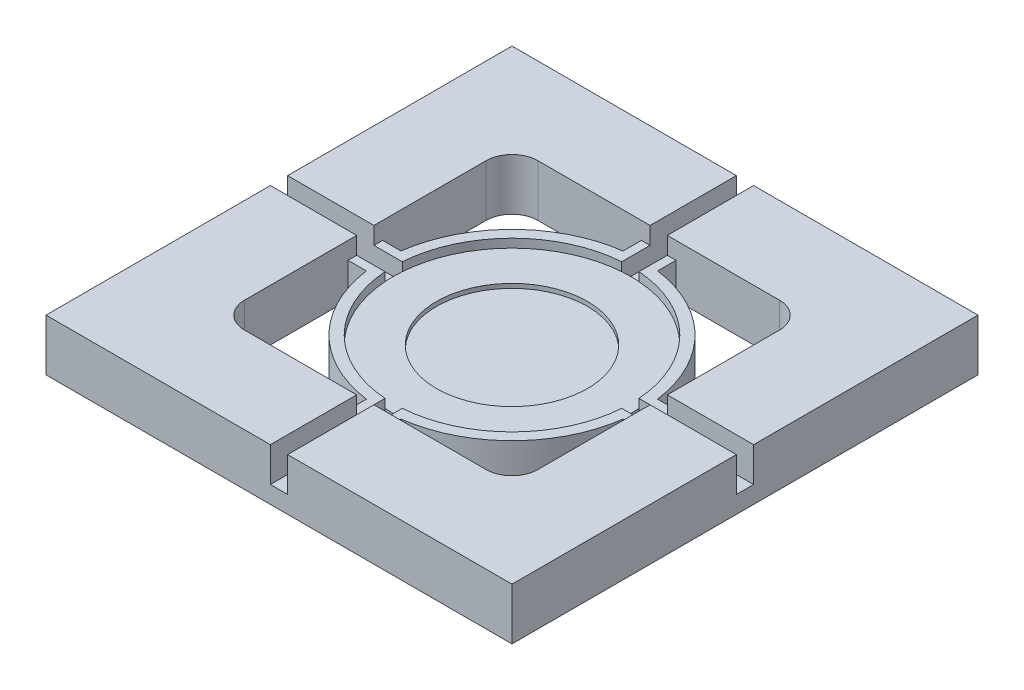
SolidWorks part; units mm, degrees
ref_plane "Front Plane" through (0, 0, 0) normal (0, 0, 1) x (1, 0, 0)
ref_plane "Top Plane" through (0, 0, 0) normal (0, 1, 0) x (1, 0, 0)
ref_plane "Right Plane" through (0, 0, 0) normal (1, 0, 0) x (0, 0, -1)
sketch "Sketch1" plane through (0, 0, 0) normal (0, 1, 0) x (1, 0, 0)
  line L6 (-27, -27) -> (27, -27)
  line L11 (-27, -27) -> (-27, 27)
  line L12 (-27, 27) -> (27, 27)
  line L76 (27, -27) -> (27, 27)
  line L77 (-27, -27) -> (27, 27) construction
  line L78 (-27, 27) -> (27, -27) construction
  point P0 (0, 0)
  dimension "D1" = 54
extrude "Boss-Extrude1" add sketch "Sketch1" along normal blind 10
sketch "Sketch2" plane through (0, 10, 0) normal (0, 1, 0) x (1, 0, 0)
  line L0 (27, 27) -> (-27, 27) construction
  line L1 (-27, 27) -> (-27, -27) construction
  line L2 (-14, -17) -> (14, -17)
  line L3 (-17, -14) -> (-17, 14)
  line L4 (-14, 17) -> (14, 17)
  line L5 (17, -14) -> (17, 14)
  line L6 (-17, -17) -> (17, 17) construction
  line L7 (-17, 17) -> (17, -17) construction
  line L8 (15, 0) -> (17, 0) construction
  line L9 (14.8661, -2) -> (17, -2)
  line L10 (14.8661, 2) -> (17, 2)
  line L11 (15, 2) -> (17, 2) construction
  line L12 (15, -2) -> (17, -2) construction
  line L13 (2, -14.8661) -> (2, -17)
  line L14 (-2, -14.8661) -> (-2, -17)
  line L15 (-14.8661, -2) -> (-17, -2)
  line L16 (-14.8661, 2) -> (-17, 2)
  line L17 (-2, 14.8661) -> (-2, 17)
  line L18 (2, 14.8661) -> (2, 17)
  arc A0 (-2, 14.8661) -> (-14.8661, 2) centre (0, 0) ccw
  arc A1 (-14.8661, -2) -> (-2, -14.8661) centre (0, 0) ccw
  arc A2 (2, -14.8661) -> (14.8661, -2) centre (0, 0) ccw
  arc A3 (14.8661, 2) -> (2, 14.8661) centre (0, 0) ccw
  arc A4 (-14, -17) -> (-17, -14) centre (-14, -14) cw
  arc A5 (14, -17) -> (17, -14) centre (14, -14) ccw
  arc A6 (14, 17) -> (17, 14) centre (14, 14) cw
  arc A7 (-17, 14) -> (-14, 17) centre (-14, 14) cw
  point P4 (0, 0)
  dimension "D3" = 30
  dimension "D8" = 3
  dimension "D1" = 34
  dimension "D2" = 10
  dimension "D7" = 10
  dimension "D4" = 2
  dimension "D5" = 2
  dimension "D6" = 4
extrude "Cut-Extrude2" cut sketch "Sketch2" against normal through all contours A3 L10 L5 L4 L18 | A2 L13 L2 L5 L9 | A1 L15 L3 L2 L14 | A0 L17 L4 L3 L16
sketch "Sketch3" plane through (0, 10, 0) normal (0, 1, 0) x (1, 0, 0)
  line L5 (-14, -17) -> (14, -17)
  line L6 (-17, -14) -> (-17, 14)
  line L7 (-14, 17) -> (14, 17)
  line L8 (17, -14) -> (17, 14)
  line L9 (-17, -17) -> (17, 17) construction
  line L10 (-17, 17) -> (17, -17) construction
  arc A0 (-17, 14) -> (-14, 17) centre (-14, 14) cw
  arc A1 (-14, -17) -> (-17, -14) centre (-14, -14) cw
  arc A2 (14, -17) -> (17, -14) centre (14, -14) ccw
  arc A3 (14, 17) -> (17, 14) centre (14, 14) cw
  point P0 (0, 0)
  dimension "D1" = 3
  dimension "D2" = 28
extrude "Cut-Extrude3" cut sketch "Sketch3" against normal blind 2
sketch "Sketch4" plane through (0, 8, 0) normal (0, 1, 0) x (1, 0, 0)
  circle A0 centre (0, 0) radius 13.75
  dimension "D1" = 27.5
extrude "Cut-Extrude4" cut sketch "Sketch4" against normal blind 1
sketch "Sketch5" plane through (0, 10, 0) normal (0, 1, 0) x (1, 0, 0)
  line L0 (-13.75, 0) -> (-27, 0) construction
  line L1 (-27, 27) -> (-27, -27) construction
  line L2 (0, 27) -> (0, 13.75) construction
  line L3 (27, 27) -> (-27, 27) construction
  line L4 (27, -27) -> (27, 27) construction
  line L5 (-14, 17) -> (14, 17) construction
  line L8 (-1, 27) -> (-1, 13.7136)
  line L9 (-27, -1) -> (-13.7136, -1)
  line L10 (1, 27) -> (1, 13.7136)
  line L11 (-27, 1) -> (-13.7136, 1)
  line L12 (-1, 27) -> (1, 27)
  line L14 (-27, -1) -> (-27, 1)
  line L16 (13.7136, 1) -> (27, 1)
  line L18 (13.75, 0) -> (27, 0) construction
  line L20 (13.7136, -1) -> (27, -1)
  line L22 (1, -13.7136) -> (1, -27)
  line L23 (1, 27) -> (1, -100) construction
  line L24 (0, -13.75) -> (0, -27) construction
  line L25 (0, 27) -> (0, -100) construction
  line L26 (-1, -13.7136) -> (-1, -27)
  line L27 (-1, 27) -> (-1, -100) construction
  line L29 (-1, 27) -> (1, 27)
  line L32 (-27, 1) -> (-27, -1)
  line L33 (-1, -27) -> (1, -27)
  line L34 (27, 1) -> (27, -1)
  line L35 (-14, -17) -> (14, -17) construction
  circle A0 centre (0, 0) radius 13.75 construction
  arc A1 (1, 13.7136) -> (-1, 13.7136) centre (0, 0) ccw
  arc A2 (-13.7136, 1) -> (-13.7136, -1) centre (0, 0) ccw
  arc A3 (13.7136, -1) -> (13.7136, 1) centre (0, 0) ccw
  arc A4 (-1, -13.7136) -> (1, -13.7136) centre (0, 0) ccw
  point P9 (0, 17)
  line M4 (27, 27) -> (-27, 27)
  line M5 (-27, 27) -> (-27, -27)
  line M7 (14, -17) -> (-14, -17)
  line M8 (-17, -14) -> (-17, 14)
  line M9 (-14, 17) -> (14, 17)
  line M10 (17, 14) -> (17, -14)
  dimension "D1" = 0
  dimension "D2" = 1
  dimension "D4" = 2
  dimension "D5" = 10
  dimension "D3" = 1
extrude "Cut-Extrude5" cut sketch "Sketch5" against normal blind 4 contours L26 L33 L22 M7 | A4 L26 L22 M7 | L34 L16 L20 M10 | A3 L20 L16 M10 | A1 L10 L8 M9 | L10 L8 M4 M9 | L11 L9 M5 M8 | A2 L11 L9 M8
sketch "Sketch7" plane through (0, 7, 0) normal (0, 1, 0) x (1, 0, 0)
  circle A0 centre (0, 0) radius 8.75
  dimension "D1" = 17.5
extrude "Cut-Extrude7" cut sketch "Sketch7" against normal blind 0.5
sketch "Croquis1" plane through (0, 0, 0) normal (0, -1, 0) x (1, 0, 0)
  line L4 (27, -27) -> (27, 27)
  line L5 (27, 27) -> (-27, 27)
  line L6 (-27, 27) -> (-27, -27)
  line L7 (-27, -27) -> (27, -27)
  line L8 (27, -27) -> (27, 27)
  line L9 (27, 27) -> (-27, 27)
  line L10 (-27, 27) -> (-27, -27)
  line L11 (-27, -27) -> (27, -27)
  dimension "D1" = 0
extrude "Cortar-Extruir1" cut sketch "Croquis1" against normal offset from surface (4 mm away) 6 up to face at (-14.9459, 10, 14.9459)
